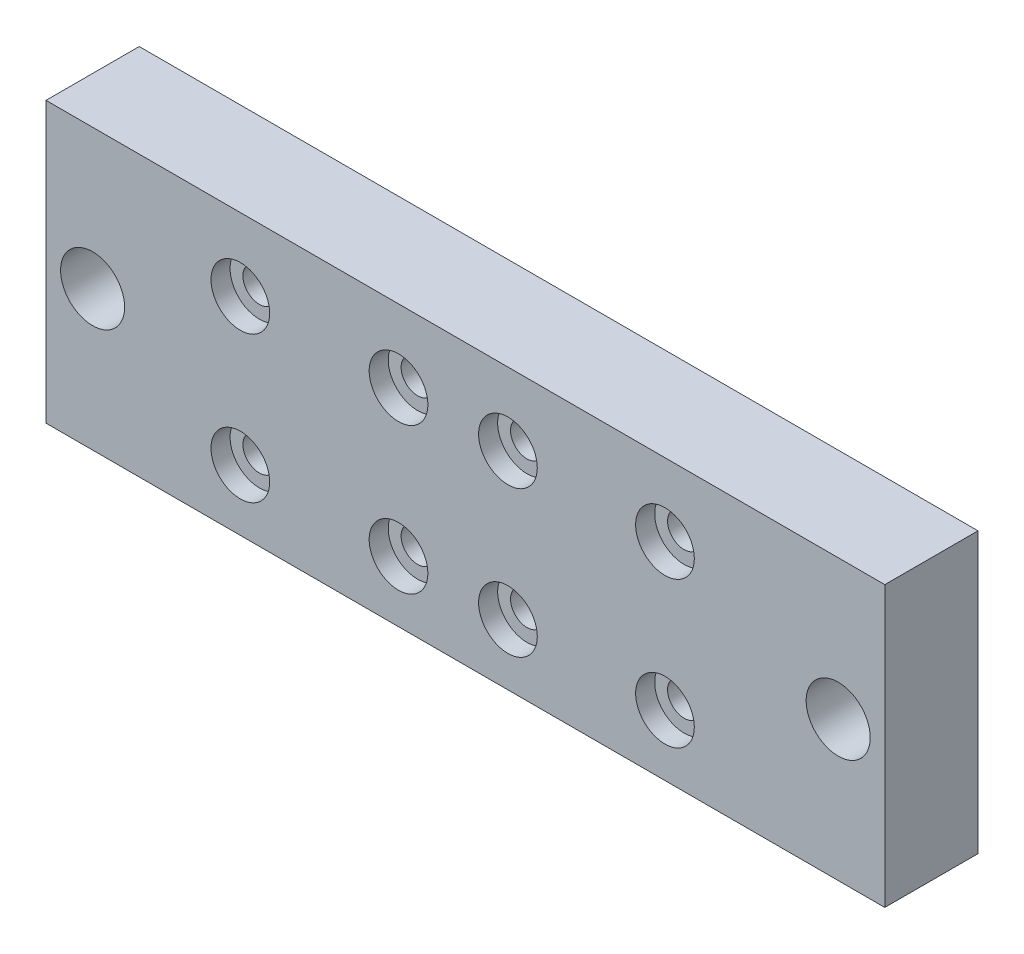
SolidWorks part; units mm, degrees
ref_plane "Front" through (0, 0, 0) normal (0, 0, 1) x (1, 0, 0)
ref_plane "Top" through (0, 0, 0) normal (0, 1, 0) x (1, 0, 0)
ref_plane "Right" through (0, 0, 0) normal (1, 0, 0) x (0, 0, -1)
sketch "Sketch1" plane through (0, 0, 0) normal (0, 0, 1) x (1, 0, 0)
  line L1 (0, 0) -> (114.3, 0)
  line L2 (0, 0) -> (0, 38.1)
  line L3 (0, 38.1) -> (114.3, 38.1)
  line L4 (114.3, 0) -> (114.3, 38.1)
  dimension "D1" = 38.1
  dimension "D2" = 114.3
extrude "Boss-Extrude1" add sketch "Sketch1" along normal blind 12.7
sketch "Sketch4" plane through (0, 0, 12.7) normal (0, 0, 1) x (1, 0, 0)
  line L0 (114.3, 38.1) -> (0, 38.1) construction
  line L1 (0, 38.1) -> (0, 0) construction
  line L2 (114.3, 0) -> (114.3, 38.1) construction
  point P0 (26.4785, 28.2048)
  point P1 (48.0366, 28.2048)
  point P2 (48.0366, 8.3033)
  point P3 (26.4785, 8.3033)
  point P4 (62.9471, 28.2048)
  point P5 (84.3456, 28.2048)
  point P6 (84.3456, 8.3033)
  point P7 (62.9471, 8.3033)
  point P8 (6.35, 19.05)
  point P9 (107.95, 19.05)
  dimension "D1" = 19.05
  dimension "D2" = 6.35
  dimension "D3" = 6.35
hole_wizard "CBORE for M4 Cheese Head Screw2" positions "3DSketch1" profile "Sketch5" counterbore size "M4" standard "AS"
sketch3d "3DSketch1"
  point P0 (26.4785, 28.2048, 12.7)
  point P3 (48.0366, 28.2048, 12.7)
  point P6 (62.9471, 28.2048, 12.7)
  point P9 (84.3456, 28.2048, 12.7)
  point P12 (84.3456, 8.3033, 12.7)
  point P15 (62.9471, 8.3033, 12.7)
  point P18 (48.0366, 8.3033, 12.7)
  point P21 (26.4785, 8.3033, 12.7)
sketch "Sketch5" plane through (26.4785, 28.2048, 12.7) normal (1, 0, 0) x (0, -1, 0)
  line L0 (0, 0) -> (0, 44.5319)
  line L1 (0, 44.5319) -> (2.25, 43.18)
  line L2 (2.25, 43.18) -> (2.25, 2.6)
  line L3 (2.25, 2.6) -> (4, 2.6)
  line L4 (4, 2.6) -> (4, 0)
  line L5 (4, 0) -> (0, 0)
  line L10 (0, 44.5319) -> (-2.25, 43.18) construction
  line L11 (0, -6.35) -> (0, 107.95) construction
  dimension "Hole Dia." = 4.5
  dimension "Hole Depth" = 43.18
  dimension "C'Bore Dia." = 8
  dimension "C'Bore Depth" = 2.6
  dimension "Drill Angle" = 118
hole_wizard "11/32 (0.34375) Diameter Hole1" positions "3DSketch2" profile "Sketch6" hole size "11/32" standard "ANSI Inch" end condition through all
sketch3d "3DSketch2"
  point P0 (46.2031, 61.3867, 0)
  point P2 (6.35, 19.05, 12.7)
  point P5 (107.95, 19.05, 12.7)
sketch "Sketch6" plane through (6.35, 19.05, 12.7) normal (1, 0, 0) x (0, -1, 0)
  line L0 (0, 0) -> (0, 12.7)
  line L1 (0, 12.7) -> (4.3656, 12.7)
  line L2 (4.3656, 12.7) -> (4.3656, 0)
  line L5 (4.3656, 0) -> (0, 0)
  line L11 (0, -6.35) -> (0, 107.95) construction
  dimension "Thru Hole Dia." = 8.7312
  dimension "Thru Hole Depth" = 12.7
